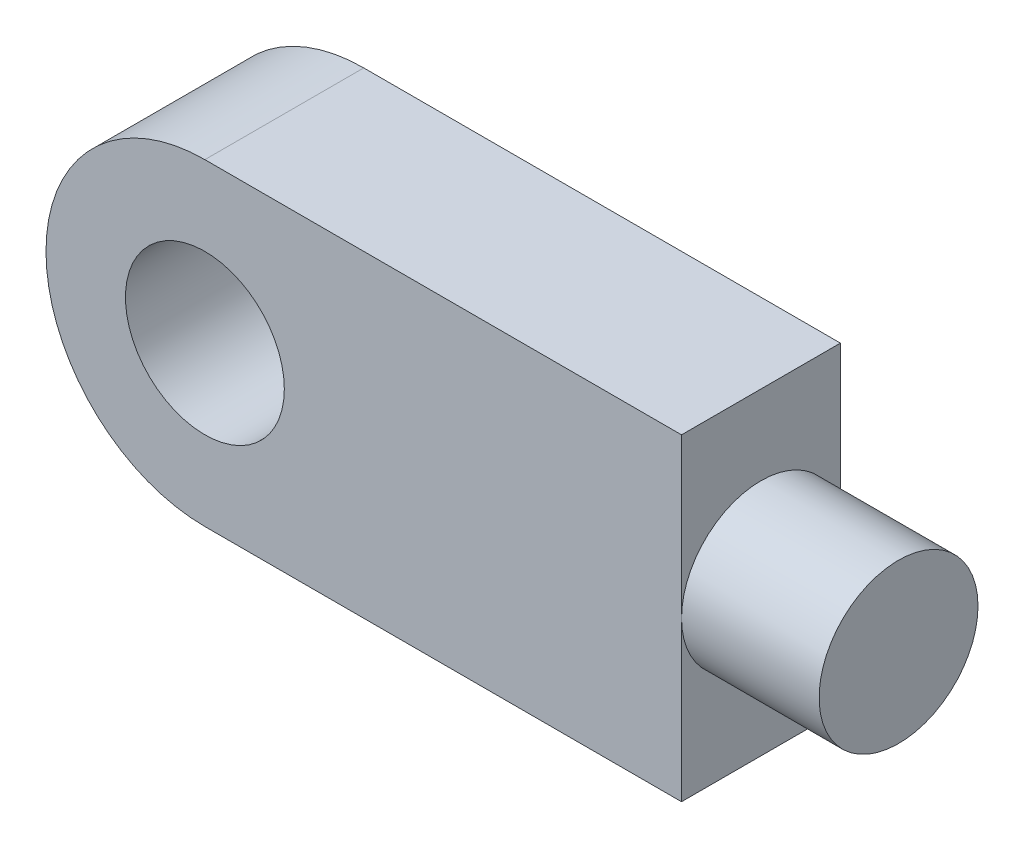
SolidWorks part; units mm, degrees
ref_plane "Front Plane" through (0, 0, 0) normal (0, 0, 1) x (1, 0, 0)
ref_plane "Top Plane" through (0, 0, 0) normal (0, 1, 0) x (1, 0, 0)
ref_plane "Right Plane" through (0, 0, 0) normal (1, 0, 0) x (0, 0, -1)
sketch "Sketch1" plane through (0, 0, 0) normal (0, 0, 1) x (1, 0, 0)
  line L0 (-75, 0) -> (75, 0) construction
  line L1 (-75, 50) -> (75, 50)
  line L2 (-75, -50) -> (75, -50)
  arc A0 (-75, 50) -> (-75, -50) centre (-75, 0) ccw
  arc A1 (75, -50) -> (75, 50) centre (75, 0) ccw
  circle A2 centre (-75, 0) radius 25
  point P3 (0, 0)
  dimension "D1" = 50
  dimension "D2" = 50
  dimension "D3" = 75
extrude "Boss-Extrude1" add sketch "Sketch1" along normal mid plane 50
ref_plane "Plane1" through (75, 0, 0) normal (1, 0, 0) x (0, 0, -1)
sketch "Sketch2" plane through (75, 0, 0) normal (1, 0, 0) x (0, 0, -1)
  line L1 (-25, 50) -> (25, 50)
  line L2 (-25, 50) -> (-25, -50)
  line L3 (-25, -50) -> (25, -50)
  line L4 (25, 50) -> (25, -50)
  circle A0 centre (0, 0) radius 25
  dimension "D1" = 50
extrude "Cut-Extrude1" cut sketch "Sketch2" along normal blind 50 contours A0 L4 L1 L2 | A0 L2 L3 L4
sketch "Sketch3" plane through (0, 0, 0) normal (0, 0, 1) x (1, 0, 0)
  line L0 (118.3013, 25) -> (75, 25) construction
  line L1 (118.3013, 25) -> (125, 25)
  line L2 (118.3013, 25) -> (118.3013, -25)
  line L3 (118.3013, -25) -> (125, -25)
  line L4 (125, 25) -> (125, -25)
  line L5 (75, -25) -> (118.3013, -25) construction
  arc A0 (118.3013, -25) -> (118.3013, 25) centre (75, 0) ccw construction
extrude "Cut-Extrude2" cut sketch "Sketch3" against normal up to next and the other way up to next
